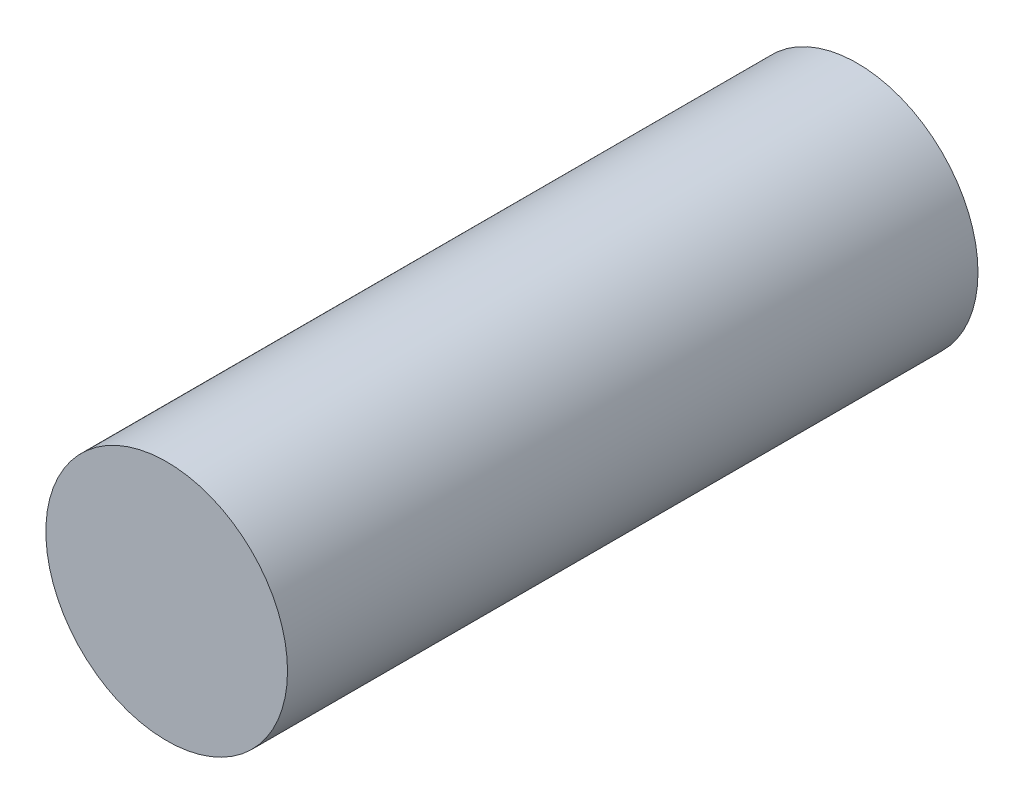
SolidWorks part; units mm, degrees
ref_plane "Front Plane" through (0, 0, 0) normal (0, 0, 1) x (1, 0, 0)
ref_plane "Top Plane" through (0, 0, 0) normal (0, 1, 0) x (1, 0, 0)
ref_plane "Right Plane" through (0, 0, 0) normal (1, 0, 0) x (0, 0, -1)
sketch "Sketch1" plane through (0, 0, 0) normal (0, 0, 1) x (1, 0, 0)
  circle A0 centre (0, 0) radius 7
  dimension "D1" = 14
extrude "Boss-Extrude1" add sketch "Sketch1" along normal blind 40
